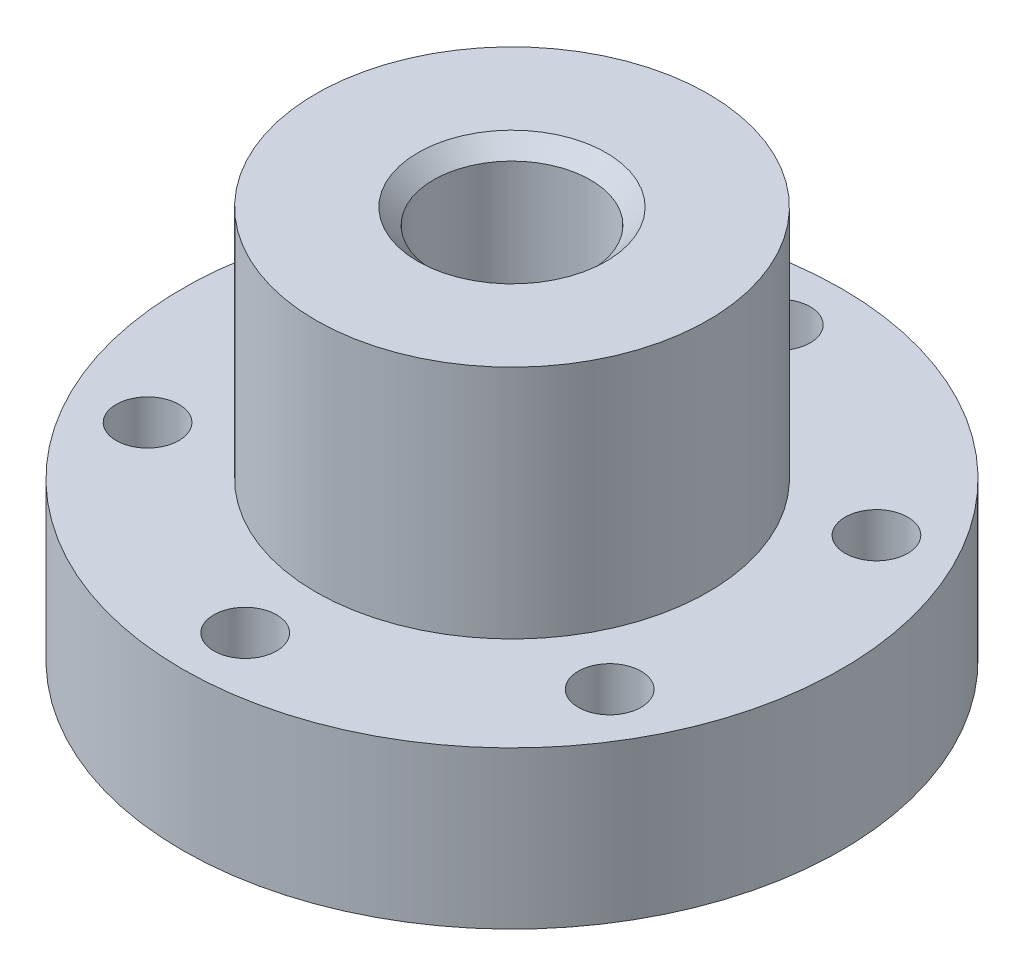
SolidWorks part; units mm, degrees
ref_plane "Front Plane" through (0, 0, 0) normal (0, 0, 1) x (1, 0, 0)
ref_plane "Top Plane" through (0, 0, 0) normal (0, 1, 0) x (1, 0, 0)
ref_plane "Right Plane" through (0, 0, 0) normal (1, 0, 0) x (0, 0, -1)
sketch "Sketch1" plane through (0, 0, 0) normal (0, 1, 0) x (1, 0, 0)
  circle A0 centre (0, 0) radius 21
  circle A1 centre (0, 17) radius 2
  circle A2 centre (14.7224, 8.5) radius 2
  circle A3 centre (14.7224, -8.5) radius 2
  circle A4 centre (0, -17) radius 2
  circle A5 centre (-14.7224, -8.5) radius 2
  circle A6 centre (-14.7224, 8.5) radius 2
  point P6 (0, 0)
  point P7 (0, -11.9885)
  point P17 (0, 0)
  dimension "D1" = 42
  dimension "D2" = 4
  dimension "D3" = 17
  dimension "D5" = 17
  dimension "D4" = 6
extrude "Boss-Extrude1" add sketch "Sketch1" along normal blind 10
sketch "Sketch2" plane through (0, 10, 0) normal (0, 1, 0) x (1, 0, 0)
  circle A0 centre (0, 0) radius 12.5
  dimension "D1" = 25
extrude "Boss-Extrude2" add sketch "Sketch2" along normal blind 15
sketch "Sketch3" plane through (0, 25, 0) normal (0, 1, 0) x (1, 0, 0)
  circle A0 centre (0, 0) radius 5
  dimension "D1" = 10
extrude "Cut-Extrude1" cut sketch "Sketch3" against normal through all
chamfer "Chamfer1" distance 1 angle 45 2 edges at (0, 0, 5) (0, 25, 5)
